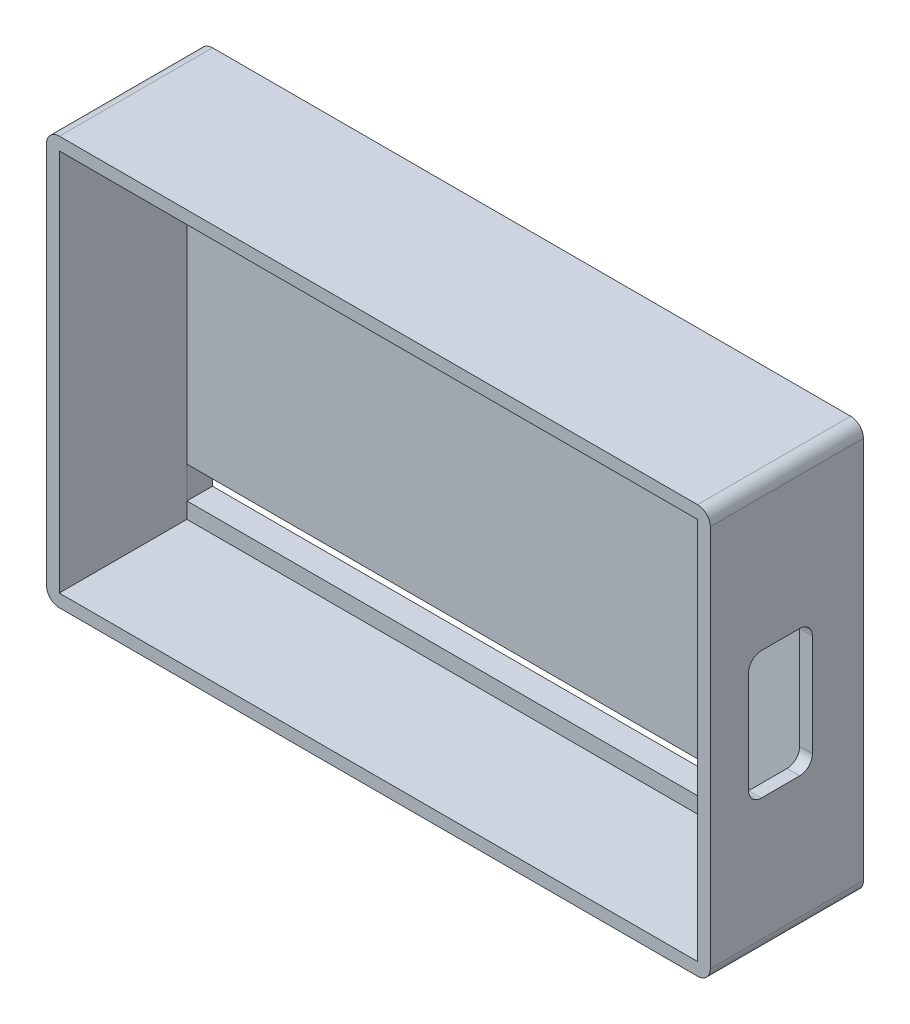
SolidWorks part; units mm, degrees
ref_plane "Front Plane" through (0, 0, 0) normal (0, 0, 1) x (1, 0, 0)
ref_plane "Top Plane" through (0, 0, 0) normal (0, 1, 0) x (1, 0, 0)
ref_plane "Right Plane" through (0, 0, 0) normal (1, 0, 0) x (0, 0, -1)
sketch "Sketch1" plane through (0, 0, 0) normal (0, 0, 1) x (1, 0, 0)
  line L1 (-25, 15) -> (25, 15) construction
  line L2 (-25, 15) -> (-25, -15) construction
  line L3 (-25, -15) -> (25, -15) construction
  line L4 (25, 15) -> (25, -15) construction
  line L5 (-25, 15) -> (25, -15) construction
  line L6 (-25, -15) -> (25, 15) construction
  line L7 (-26, 16) -> (26, 16)
  line L8 (-26, 16) -> (-26, -16)
  line L9 (-26, -16) -> (26, -16)
  line L10 (26, 16) -> (26, -16)
  line L11 (-26, 16) -> (26, -16) construction
  line L12 (-26, -16) -> (26, 16) construction
  line L13 (-25, 13.75) -> (25, 13.75)
  line L14 (-25, 13.75) -> (-25, 11.25)
  line L15 (-25, 11.25) -> (25, 11.25)
  line L16 (25, 13.75) -> (25, 11.25)
  line L17 (-25, 13.75) -> (25, 11.25) construction
  line L18 (-25, 11.25) -> (25, 13.75) construction
  line L19 (-25, -11.25) -> (25, -11.25)
  line L20 (-25, -11.25) -> (-25, -13.75)
  line L21 (-25, -13.75) -> (25, -13.75)
  line L22 (25, -11.25) -> (25, -13.75)
  line L23 (-25, -11.25) -> (25, -13.75) construction
  line L24 (-25, -13.75) -> (25, -11.25) construction
  point P0 (0, 0)
  point P6 (0, 0)
  point P11 (0, 12.5)
  point P16 (0, -12.5)
  dimension "D1" = 30
  dimension "D2" = 50
  dimension "D3" = 32
  dimension "D4" = 52
  dimension "D5" = 2.5
  dimension "D6" = 2.5
  dimension "D7" = 27.5
  dimension "D8" = 13.75
extrude "Boss-Extrude1" add sketch "Sketch1" along normal blind 2
sketch "Sketch2" plane through (0, 0, 2) normal (0, 0, 1) x (1, 0, 0)
  line L1 (-26, 16) -> (26, 16)
  line L2 (-26, 16) -> (-26, -16)
  line L3 (-26, -16) -> (26, -16)
  line L4 (26, 16) -> (26, -16)
  line L5 (-26, 16) -> (26, -16) construction
  line L6 (-26, -16) -> (26, 16) construction
  line L7 (-25.004, 15) -> (25.004, 15)
  line L8 (-25.004, 15) -> (-25.004, -15)
  line L9 (-25.004, -15) -> (25.004, -15)
  line L10 (25.004, 15) -> (25.004, -15)
  line L11 (-25.004, 15) -> (25.004, -15) construction
  line L12 (-25.004, -15) -> (25.004, 15) construction
  point P0 (0, 0)
  point P7 (0, 0)
  dimension "D1" = 1
extrude "Boss-Extrude2" add sketch "Sketch2" along normal blind 10
sketch "Sketch3" plane through (26, 0, 0) normal (1, 0, 0) x (0, 0, -1)
  line L1 (-9, 4.5937) -> (-4, 4.5937)
  line L2 (-9, 4.5937) -> (-9, -5.4063)
  line L3 (-9, -5.4063) -> (-4, -5.4063)
  line L4 (-4, 4.5937) -> (-4, -5.4063)
  line L5 (-9, 4.5937) -> (-4, -5.4063) construction
  line L6 (-9, -5.4063) -> (-4, 4.5937) construction
  point P0 (-6.5, -0.4063)
  dimension "D1" = 10
  dimension "D2" = 5
  dimension "D3" = 4
extrude "Cut-Extrude1" cut sketch "Sketch3" against normal blind 10
fillet "Fillet1" radius 1 1 edges at (26, 16, 6)
fillet "Fillet2" radius 1 1 edges at (26, -16, 6)
fillet "Fillet3" radius 1 1 edges at (-26, -16, 6)
fillet "Fillet4" radius 1 1 edges at (-26, 16, 6)
fillet "Fillet5" radius 1 1 edges at (25.502, 4.5937, 4)
fillet "Fillet6" radius 1 1 edges at (25.502, -5.4063, 4)
fillet "Fillet7" radius 1 1 edges at (25.502, -5.4063, 9)
fillet "Fillet8" radius 1 1 edges at (25.502, 4.5937, 9)
